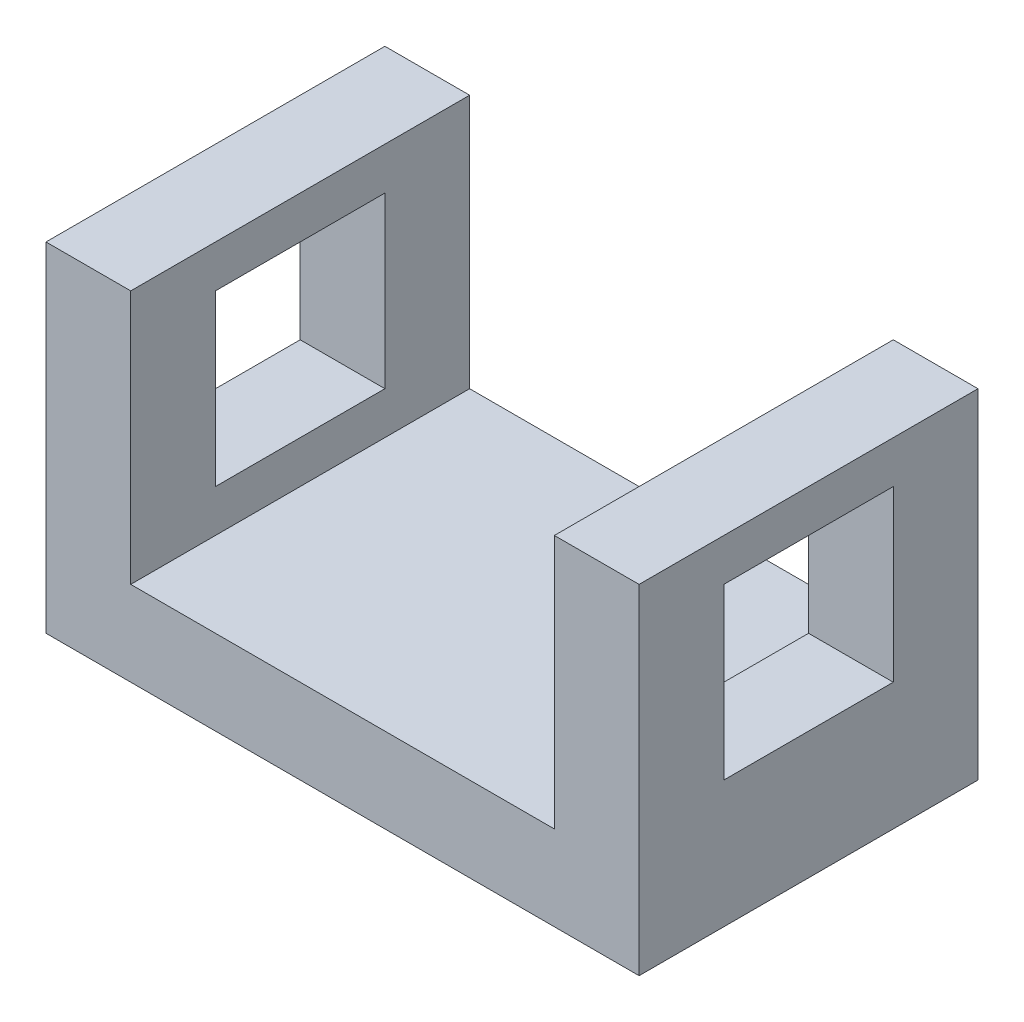
SolidWorks part; units mm, degrees
ref_plane "Front Plane" through (0, 0, 0) normal (0, 0, 1) x (1, 0, 0)
ref_plane "Top Plane" through (0, 0, 0) normal (0, 1, 0) x (1, 0, 0)
ref_plane "Right Plane" through (0, 0, 0) normal (1, 0, 0) x (0, 0, -1)
sketch "Sketch1" plane through (0, 0, 0) normal (0, 0, 1) x (1, 0, 0)
  line L0 (-62.4703, -14.9094) -> (26.4297, -14.9094)
  line L1 (26.4297, -14.9094) -> (26.4297, 35.8906)
  line L2 (26.4297, 35.8906) -> (13.7297, 35.8906)
  line L3 (13.7297, 35.8906) -> (13.7297, -2.2094)
  line L4 (13.7297, -2.2094) -> (-49.7703, -2.2094)
  line L5 (-49.7703, -2.2094) -> (-49.7703, 35.8906)
  line L6 (-49.7703, 35.8906) -> (-62.4703, 35.8906)
  line L7 (-62.4703, 35.8906) -> (-62.4703, -14.9094)
  dimension "D1" = 88.9
  dimension "D2" = 50.8
  dimension "D3" = 12.7
  dimension "D4" = 12.7
extrude "Boss-Extrude1" add sketch "Sketch1" along normal mid plane 50.8
sketch "Sketch3" plane through (0, 0, 0) normal (1, 0, 0) x (0, 0, -1)
  line L0 (12.7, 29.5406) -> (-12.7, 29.5406)
  line L1 (-12.7, 29.5406) -> (-12.7, 4.1406)
  line L2 (-12.7, 4.1406) -> (12.7, 4.1406)
  line L3 (12.7, 4.1406) -> (12.7, 29.5406)
  line L4 (-25.4, -14.9094) -> (-25.4, 35.8906) construction
  line L5 (-25.4, 35.8906) -> (25.4, 35.8906) construction
  dimension "D1" = 12.7
  dimension "D2" = 6.35
  dimension "D3" = 25.4
extrude "Cut-Extrude1" cut sketch "Sketch3" against normal mid plane 152.4
